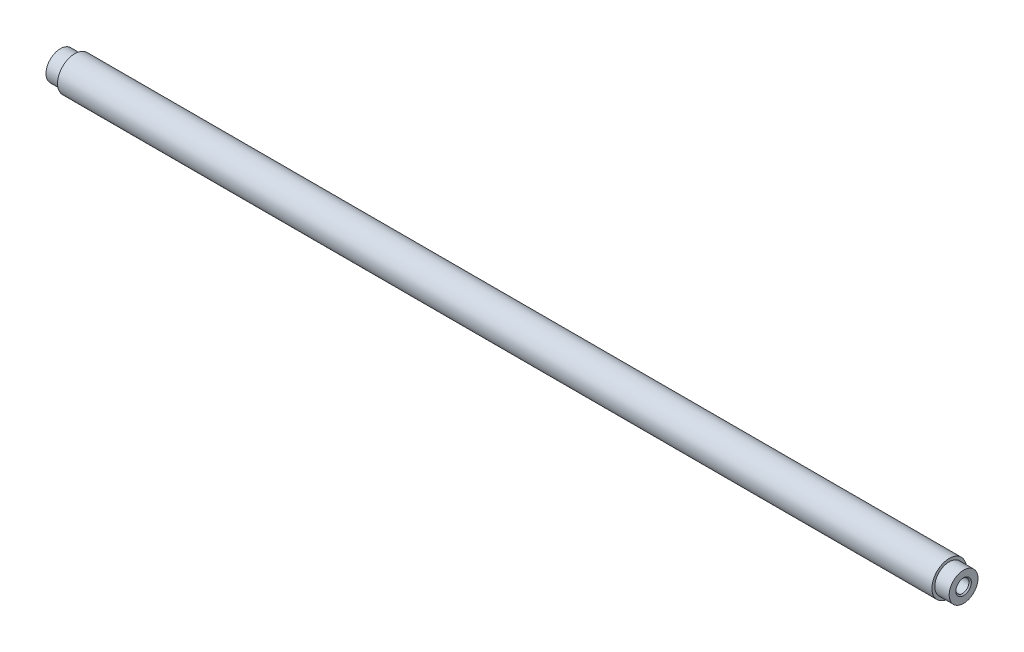
SolidWorks part; units mm, degrees
ref_plane "Ön Düzlem" through (0, 0, 0) normal (0, 0, 1) x (1, 0, 0)
ref_plane "Üst Düzlem" through (0, 0, 0) normal (0, 1, 0) x (1, 0, 0)
ref_plane "Sağ Düzlem" through (0, 0, 0) normal (1, 0, 0) x (0, 0, -1)
sketch "Sketch1" plane through (0, 0, 0) normal (0, 0, 1) x (1, 0, 0)
  line L0 (-235, 0) -> (235, 0)
  line L1 (-235, 0) -> (-235, 7.5)
  line L2 (-235, 7.5) -> (-227.5, 7.5)
  line L3 (-227.5, 7.5) -> (-227.5, 9)
  line L4 (-227.5, 9) -> (227.5, 9)
  line L5 (227.5, 9) -> (227.5, 7.5)
  line L6 (227.5, 7.5) -> (235, 7.5)
  line L7 (235, 7.5) -> (235, 0)
  dimension "D1" = 470
  dimension "D2" = 7.5
  dimension "D3" = 9
  dimension "D4" = 455
revolve "Revolve1" add sketch "Sketch1" angle 360 about L0
hole_wizard "M8 Tapped Hole2" positions "Sketch4" profile "Sketch5" tap size "M8" standard "ISO"
sketch "Sketch4" plane through (235, 0, 0) normal (1, 0, 0) x (0, 0, -1)
  point P0 (0, 0)
sketch "Sketch5" plane through (235, 0, 0) normal (0, 1, 0) x (0, 0, -1)
  line L0 (0, 0) -> (0, 22.0429)
  line L1 (0, 22.0429) -> (3.4, 20)
  line L2 (3.4, 20) -> (3.4, 0.625)
  line L3 (3.4, 0.625) -> (4.025, 0)
  line L5 (4.025, 0) -> (0, 0)
  line L6 (-3.4, 0.625) -> (-4.025, 0) construction
  line L10 (0, 22.0429) -> (-3.4, 20) construction
  line L11 (0, -6.35) -> (0, 107.95) construction
  dimension "Tap Drill Dia." = 6.8
  dimension "Tap Drill Depth" = 20
  dimension "Near C'Sink Dia." = 8.05
  dimension "Near C'Sink Angle" = 90
  dimension "Drill Angle" = 118
cosmetic thread "Hole Thread2" parameters "D1"=16, "D2"=8
mirror "Mirror1" about plane through (0, 0, 0) normal (1, 0, 0) of "M8 Tapped Hole2"
cosmetic thread "Hole Thread3" parameters "D1"=16, "D2"=8
